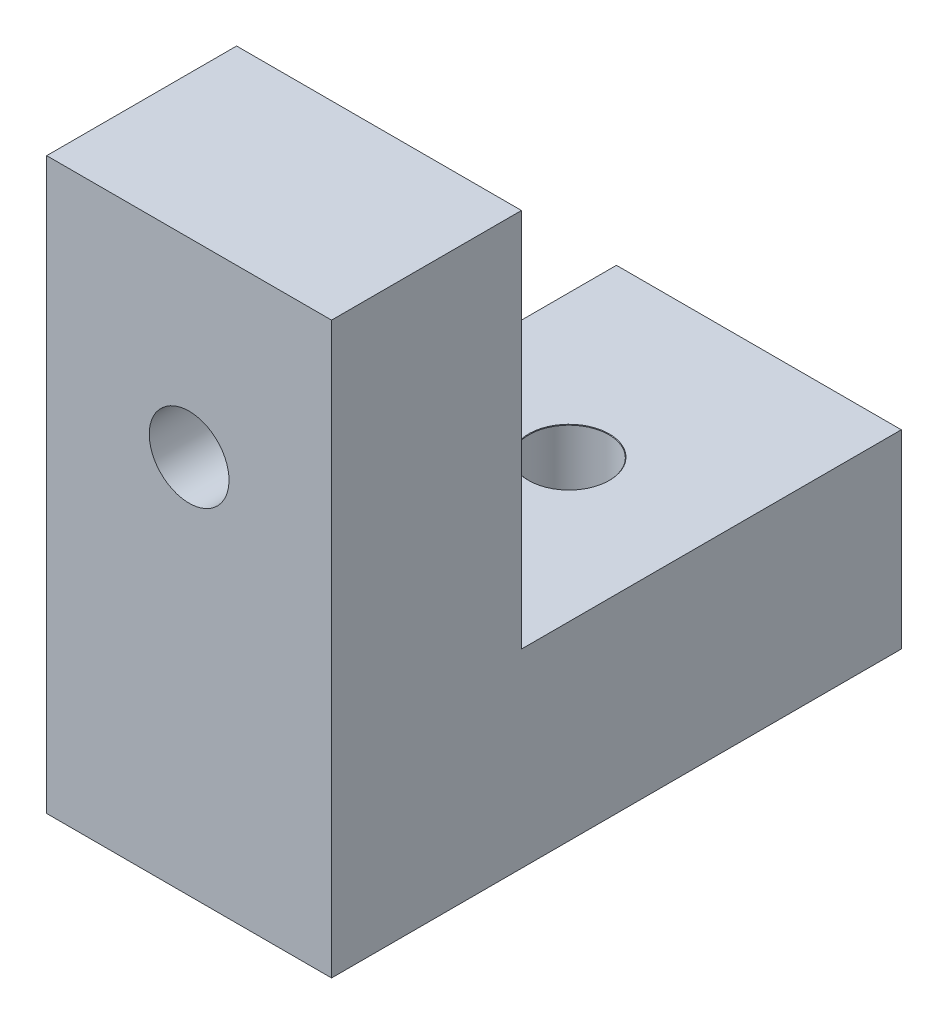
SolidWorks part; units mm, degrees
ref_plane "Front Plane" through (0, 0, 0) normal (0, 0, 1) x (1, 0, 0)
ref_plane "Top Plane" through (0, 0, 0) normal (0, 1, 0) x (1, 0, 0)
ref_plane "Right Plane" through (0, 0, 0) normal (1, 0, 0) x (0, 0, -1)
sketch "Sketch8" plane through (0, 0, 0) normal (1, 0, 0) x (0, 0, -1)
  line L1 (0, 0) -> (30, 0)
  line L2 (0, 0) -> (0, 30)
  line L3 (0, 30) -> (30, 30)
  line L4 (30, 0) -> (30, 30)
  line L5 (15, 30) -> (30, 30)
  line L8 (30, 30) -> (30, 15)
  line L9 (30, 30) -> (10, 30)
  line L10 (30, 30) -> (30, 10)
  line L11 (30, 10) -> (10, 10)
  line L12 (10, 30) -> (10, 10)
extrude "Boss-Extrude2" add sketch "Sketch8" along normal blind 15 contours L12 L3 L2 L1 L4 L11
sketch "Sketch9" plane through (0, 10, 0) normal (0, 1, 0) x (1, 0, 0)
  line L0 (0, 10) -> (0, 20)
  line L1 (0, 30) -> (0, 10) construction
  line L4 (0, 25) -> (0, 20)
hole_wizard "Tap Drill for M5x0.8 Tap3" positions "Sketch10" profile "Sketch11" hole size "M5x0.8" standard "ANSI Metric" end condition through all
sketch "Sketch10" plane through (0, 10, 0) normal (0, 1, 0) x (1, 0, 0)
  point P0 (7.5, 20)
sketch "Sketch11" plane through (7.5, 10, -20) normal (1, 0, 0) x (0, 0, 1)
  line L0 (0, 0) -> (0, 10)
  line L1 (0, 10) -> (2.1, 10)
  line L2 (2.1, 10) -> (2.1, 0.025)
  line L3 (2.1, 0.025) -> (2.125, 0)
  line L5 (2.125, 0) -> (0, 0)
  line L6 (-2.1, 0.025) -> (-2.125, 0) construction
  line L11 (0, -6.35) -> (0, 107.95) construction
  dimension "Thru Hole Dia." = 4.2
  dimension "Thru Hole Depth" = 10
  dimension "Near C'Sink Dia." = 4.25
  dimension "Near C'Sink Angle" = 90
hole_wizard "Tap Drill for M5x0.8 Tap4" positions "Sketch12" profile "Sketch13" hole size "M5x0.8" standard "ANSI Metric" end condition through all
sketch "Sketch12" plane through (0, 0, -10) normal (0, 0, -1) x (-1, 0, 0)
  point P0 (-7.5, 20)
sketch "Sketch13" plane through (7.5, 20, -10) normal (1, 0, 0) x (0, 1, 0)
  line L0 (0, 0) -> (0, 10)
  line L1 (0, 10) -> (2.1, 10)
  line L2 (2.1, 10) -> (2.1, 0.025)
  line L3 (2.1, 0.025) -> (2.125, 0)
  line L5 (2.125, 0) -> (0, 0)
  line L6 (-2.1, 0.025) -> (-2.125, 0) construction
  line L11 (0, -6.35) -> (0, 107.95) construction
  dimension "Thru Hole Dia." = 4.2
  dimension "Thru Hole Depth" = 10
  dimension "Near C'Sink Dia." = 4.25
  dimension "Near C'Sink Angle" = 90
